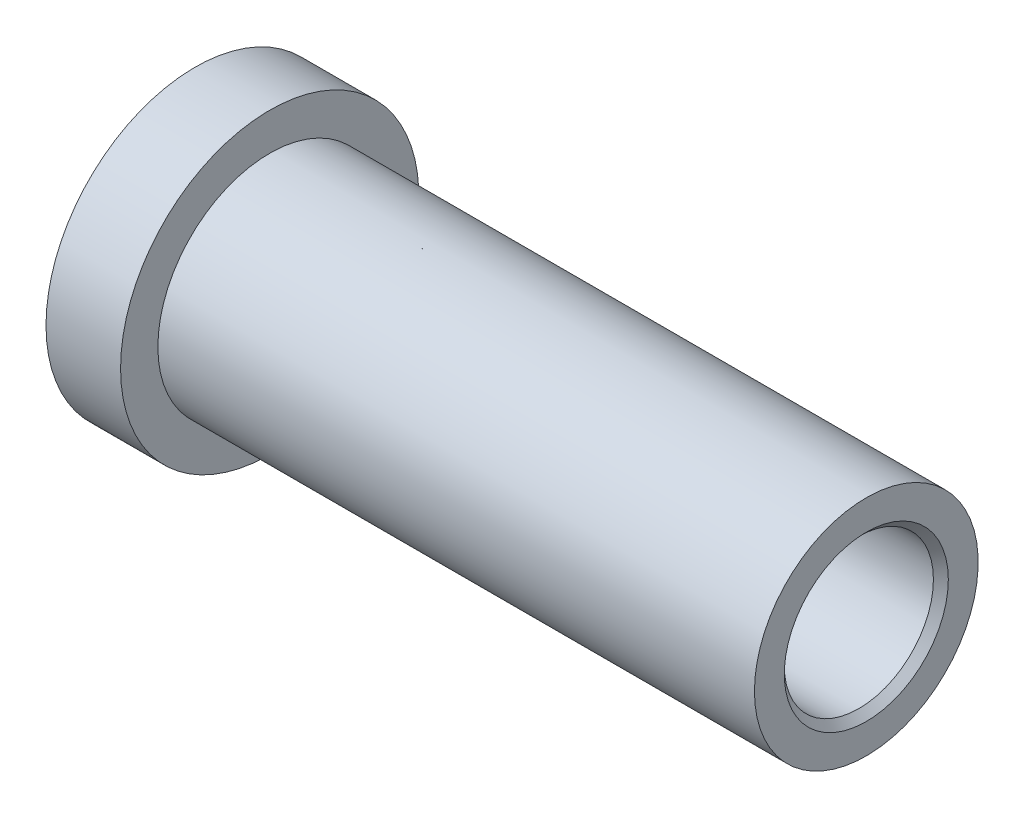
SolidWorks part; units mm, degrees
ref_plane "Спереди" through (0, 0, 0) normal (0, 0, 1) x (1, 0, 0)
ref_plane "Сверху" through (0, 0, 0) normal (0, 1, 0) x (1, 0, 0)
ref_plane "Справа" through (0, 0, 0) normal (1, 0, 0) x (0, 0, -1)
sketch "Эскиз1" plane through (0, 0, 0) normal (0, 0, 1) x (1, 0, 0)
  line L0 (0, 0) -> (0, 5) construction
  line L1 (0, 5) -> (0, 10)
  line L2 (0, 10) -> (5, 10)
  line L3 (5, 10) -> (5, 7.5)
  line L4 (5, 7.5) -> (45, 7.5)
  line L5 (45, 7.5) -> (45, 5)
  line L6 (45, 5) -> (0, 5) construction
  line L7 (0, 0) -> (45, 0) construction
  line L8 (45, 0) -> (45, 5)
  line L9 (0, 5) -> (45, 5)
  dimension "D1" = 5
  dimension "D2" = 10
  dimension "D3" = 7.5
  dimension "D4" = 45
  dimension "D5" = 5
revolve "Повернуть1" add sketch "Эскиз1" angle 360 about L7
chamfer "Фаска1" distance 0.5 angle 45 2 edges at (45, 0, 5) (0, 0, 5)
